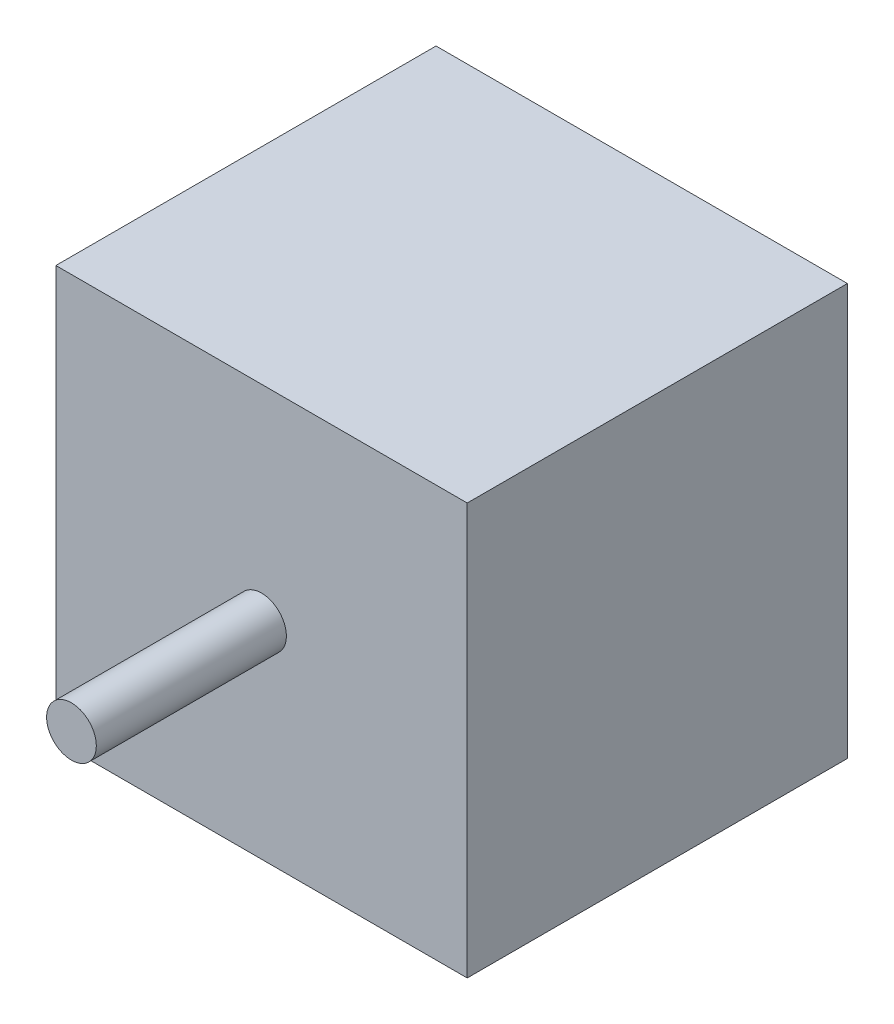
SolidWorks part; units mm, degrees
ref_plane "Front Plane" through (0, 0, 0) normal (0, 0, 1) x (1, 0, 0)
ref_plane "Top Plane" through (0, 0, 0) normal (0, 1, 0) x (1, 0, 0)
ref_plane "Right Plane" through (0, 0, 0) normal (1, 0, 0) x (0, 0, -1)
sketch "Sketch1" plane through (0, 0, 0) normal (0, 0, 1) x (1, 0, 0)
  line L1 (0, 0) -> (-42.2, 0)
  line L2 (0, 0) -> (0, -42.2)
  line L3 (0, -42.2) -> (-42.2, -42.2)
  line L4 (-42.2, 0) -> (-42.2, -42.2)
  dimension "D1" = 42.2
  dimension "D2" = 42.2
extrude "Boss-Extrude1" add sketch "Sketch1" along normal blind 39
sketch "Sketch2" plane through (0, 0, 39) normal (0, 0, 1) x (1, 0, 0)
  line L0 (-42.2, 0) -> (-42.2, -42.2) construction
  line L1 (0, 0) -> (-42.2, 0) construction
  circle A0 centre (-21.1, -21.1) radius 2.55
  dimension "D3" = 5.1
  dimension "D1" = 21.1
  dimension "D2" = 21.1
extrude "Boss-Extrude2" add sketch "Sketch2" along normal blind 19.5
